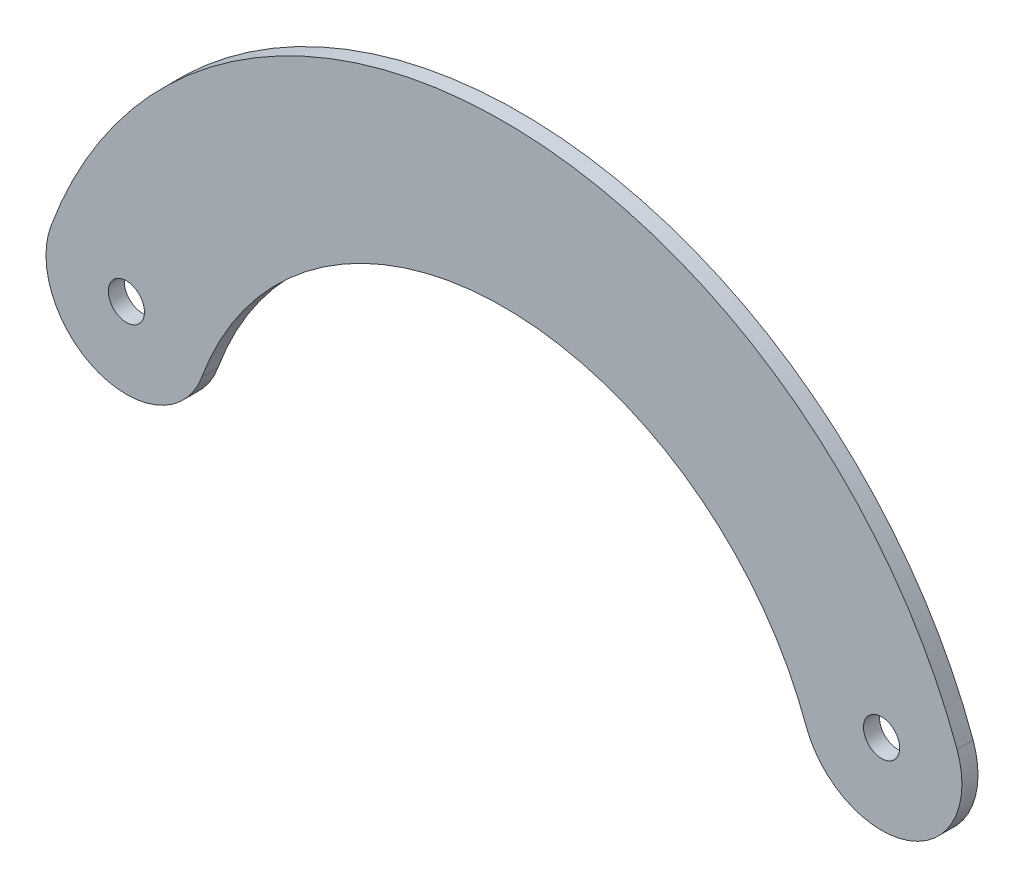
SolidWorks part; units mm, degrees
material "POLYURETHANE (11671)"
ref_plane "Face" through (0, 0, 0) normal (0, 0, 1) x (1, 0, 0)
ref_plane "Dessus" through (0, 0, 0) normal (0, 1, 0) x (1, 0, 0)
ref_plane "Droite" through (0, 0, 0) normal (1, 0, 0) x (0, 0, -1)
sketch "Esquisse1" plane through (0, 0, 0) normal (0, 0, 1) x (1, 0, 0)
  line L0 (0, 0) -> (0, 50) construction
  line L1 (0, 0) -> (46.9846, 17.101) construction
  line L2 (0, 0) -> (-46.9846, 17.101) construction
  arc A0 (46.9846, 17.101) -> (-46.9846, 17.101) centre (0, 0) ccw construction
  arc A1 (37.5877, 13.6808) -> (56.3816, 20.5212) centre (46.9846, 17.101) ccw
  arc A2 (-56.3816, 20.5212) -> (-37.5877, 13.6808) centre (-46.9846, 17.101) ccw
  arc A3 (37.5877, 13.6808) -> (-37.5877, 13.6808) centre (0, 0) ccw
  arc A4 (56.3816, 20.5212) -> (-56.3816, 20.5212) centre (0, 0) ccw
  circle A5 centre (-46.9846, 17.101) radius 2.25
  circle A6 centre (46.9846, 17.101) radius 2.25
  dimension "D1" = 70
  dimension "D2" = 70
  dimension "D5" = 4.5
  dimension "D6" = 50
  dimension "D3" = 10
  dimension "D4" = 4.5
extrude "Boss.-Extru.1" add sketch "Esquisse1" along normal blind 2
sketch "Graduations" plane through (0, 0, 2) normal (0, 0, 1) x (1, 0, 0)
  line L0 (0, 45) -> (0, 53)
  line L1 (7.8142, 44.3163) -> (9.2034, 52.1948)
  line L2 (15.3909, 42.2862) -> (18.1271, 49.8037)
  line L3 (22.5, 38.9711) -> (26.5, 45.8993)
  line L4 (28.9254, 34.472) -> (34.0677, 40.6004)
  line L5 (34.472, 28.9254) -> (40.6004, 34.0677)
  line L6 (38.9711, 22.5) -> (45.8993, 26.5)
  line L8 (11.6469, 43.4667) -> (12.6821, 47.3304)
  line L9 (-38.5725, 23.1767) -> (-40.7154, 24.4643)
  line L10 (19.0178, 40.7839) -> (20.7083, 44.4091)
  line L11 (-38.1622, 23.8464) -> (-40.2823, 25.1712)
  line L12 (3.922, 44.8288) -> (4.2706, 48.8135)
  line L13 (25.8109, 36.8618) -> (28.1052, 40.1385)
  line L14 (-37.7402, 24.5088) -> (-39.8369, 25.8704)
  line L15 (31.8198, 31.8198) -> (34.6482, 34.6482)
  line L16 (-37.3067, 25.1637) -> (-39.3793, 26.5617)
  line L17 (36.8618, 25.8109) -> (40.1385, 28.1052)
  line L19 (-36.4058, 26.4503) -> (-38.4283, 27.9198)
  line L20 (-35.9386, 27.0817) -> (-37.9352, 28.5862)
  line L21 (-35.4605, 27.7048) -> (-37.4305, 29.2439)
  line L22 (-34.9716, 28.3194) -> (-36.9144, 29.8927)
  line L24 (-33.9619, 29.5227) -> (-35.8487, 31.1628)
  line L25 (-33.4415, 30.1109) -> (-35.2994, 31.7837)
  line L26 (-32.9109, 30.6899) -> (-34.7393, 32.3949)
  line L27 (-32.3703, 31.2596) -> (-34.1686, 32.9963)
  line L29 (-31.2596, 32.3703) -> (-32.9963, 34.1686)
  line L30 (-38.9711, 22.5) -> (-45.8993, 26.5)
  line L31 (-34.472, 28.9254) -> (-40.6004, 34.0677)
  line L32 (-28.9254, 34.472) -> (-34.0677, 40.6004)
  line L33 (-22.5, 38.9711) -> (-26.5, 45.8993)
  line L34 (-15.3909, 42.2862) -> (-18.1271, 49.8037)
  line L35 (-7.8142, 44.3163) -> (-9.2034, 52.1948)
  line L36 (42.2862, 15.3909) -> (49.8037, 18.1271)
  line L37 (-42.2862, 15.3909) -> (-49.8037, 18.1271)
  line L38 (44.3163, 7.8142) -> (52.1948, 9.2034)
  line L39 (45, 0) -> (53, 0)
  line L40 (44.3163, -7.8142) -> (52.1948, -9.2034)
  line L41 (42.2862, -15.3909) -> (49.8037, -18.1271)
  line L42 (38.9711, -22.5) -> (45.8993, -26.5)
  line L43 (34.472, -28.9254) -> (40.6004, -34.0677)
  line L44 (28.9254, -34.472) -> (34.0677, -40.6004)
  line L45 (22.5, -38.9711) -> (26.5, -45.8993)
  line L46 (15.3909, -42.2862) -> (18.1271, -49.8037)
  line L47 (7.8142, -44.3163) -> (9.2034, -52.1948)
  line L48 (0, -45) -> (0, -53)
  line L49 (-7.8142, -44.3163) -> (-9.2034, -52.1948)
  line L50 (-15.3909, -42.2862) -> (-18.1271, -49.8037)
  line L51 (-22.5, -38.9711) -> (-26.5, -45.8993)
  line L52 (-28.9254, -34.472) -> (-34.0677, -40.6004)
  line L53 (-34.472, -28.9254) -> (-40.6004, -34.0677)
  line L54 (-38.9711, -22.5) -> (-45.8993, -26.5)
  line L55 (-42.2862, -15.3909) -> (-49.8037, -18.1271)
  line L56 (-44.3163, -7.8142) -> (-52.1948, -9.2034)
  line L57 (-45, 0) -> (-53, 0)
  line L58 (-44.3163, 7.8142) -> (-52.1948, 9.2034)
  line L59 (-30.6899, 32.9109) -> (-32.3949, 34.7393)
  line L60 (-30.1109, 33.4415) -> (-31.7837, 35.2994)
  line L61 (-29.5227, 33.9619) -> (-31.1628, 35.8487)
  line L63 (-28.3194, 34.9716) -> (-29.8927, 36.9144)
  line L64 (-27.7048, 35.4605) -> (-29.2439, 37.4305)
  line L65 (-27.0817, 35.9386) -> (-28.5862, 37.9352)
  line L66 (-26.4503, 36.4058) -> (-27.9198, 38.4283)
  line L68 (-25.1637, 37.3067) -> (-26.5617, 39.3793)
  line L69 (-24.5088, 37.7402) -> (-25.8704, 39.8369)
  line L70 (-23.8464, 38.1622) -> (-25.1712, 40.2823)
  line L71 (-23.1767, 38.5725) -> (-24.4643, 40.7154)
  line L73 (-21.8164, 39.3579) -> (-23.0285, 41.5444)
  line L74 (-21.1262, 39.7326) -> (-22.2999, 41.94)
  line L75 (-20.4296, 40.0953) -> (-21.5645, 42.3228)
  line L76 (-19.7267, 40.4457) -> (-20.8226, 42.6927)
  line L78 (-18.3031, 41.1095) -> (-19.32, 43.3934)
  line L79 (-17.5829, 41.4227) -> (-18.5597, 43.724)
  line L80 (-16.8573, 41.7233) -> (-17.7938, 44.0412)
  line L81 (-16.1266, 42.0111) -> (-17.0225, 44.3451)
  line L83 (-14.6506, 42.5483) -> (-15.4645, 44.9121)
  line L84 (-13.9058, 42.7975) -> (-14.6783, 45.1752)
  line L85 (-13.1567, 43.0337) -> (-13.8877, 45.4245)
  line L86 (-12.4037, 43.2568) -> (-13.0928, 45.6599)
  line L88 (-10.8865, 43.6633) -> (-11.4913, 46.089)
  line L89 (-10.1228, 43.8467) -> (-10.6852, 46.2826)
  line L90 (-9.356, 44.0166) -> (-9.8758, 46.462)
  line L91 (-8.5864, 44.1732) -> (-9.0634, 46.6273)
  line L93 (-7.0396, 44.446) -> (-7.4306, 46.9152)
  line L94 (-6.2628, 44.5621) -> (-6.6107, 47.0377)
  line L95 (-5.4841, 44.6646) -> (-5.7888, 47.1459)
  line L96 (-4.7038, 44.7535) -> (-4.9651, 47.2398)
  line L98 (-3.139, 44.8904) -> (-3.3134, 47.3843)
  line L99 (-2.3551, 44.9383) -> (-2.486, 47.4349)
  line L100 (-1.5705, 44.9726) -> (-1.6577, 47.4711)
  line L101 (-0.7854, 44.9931) -> (-0.829, 47.4928)
  line L103 (0.7854, 44.9931) -> (0.829, 47.4928)
  line L104 (-36.8618, 25.8109) -> (-40.1385, 28.1052)
  line L105 (1.5705, 44.9726) -> (1.6577, 47.4711)
  line L106 (-31.8198, 31.8198) -> (-34.6482, 34.6482)
  line L107 (2.3551, 44.9383) -> (2.486, 47.4349)
  line L108 (-25.8109, 36.8618) -> (-28.1052, 40.1385)
  line L109 (3.139, 44.8904) -> (3.3134, 47.3843)
  line L110 (-19.0178, 40.7839) -> (-20.7083, 44.4091)
  line L112 (-11.6469, 43.4667) -> (-12.6821, 47.3304)
  line L113 (4.7038, 44.7535) -> (4.9651, 47.2398)
  line L114 (-3.922, 44.8288) -> (-4.2706, 48.8135)
  line L115 (5.4841, 44.6646) -> (5.7888, 47.1459)
  line L116 (42.2862, 15.3909) -> (46.0449, 16.759)
  line L117 (43.4667, 11.6469) -> (47.3304, 12.6821)
  line L118 (44.3163, 7.8142) -> (48.2556, 8.5088)
  line L119 (44.8288, 3.922) -> (48.8135, 4.2706)
  line L120 (45, 0) -> (49, 0)
  line L121 (44.8288, -3.922) -> (48.8135, -4.2706)
  line L122 (44.3163, -7.8142) -> (48.2556, -8.5088)
  line L123 (43.4667, -11.6469) -> (47.3304, -12.6821)
  line L124 (42.2862, -15.3909) -> (46.0449, -16.759)
  line L125 (40.7839, -19.0178) -> (44.4091, -20.7083)
  line L126 (38.9711, -22.5) -> (42.4352, -24.5)
  line L127 (-38.9711, -22.5) -> (-42.4352, -24.5)
  line L128 (-40.7839, -19.0178) -> (-44.4091, -20.7083)
  line L129 (-42.2862, -15.3909) -> (-46.0449, -16.759)
  line L130 (-43.4667, -11.6469) -> (-47.3304, -12.6821)
  line L131 (-44.3163, -7.8142) -> (-48.2556, -8.5088)
  line L132 (-44.8288, -3.922) -> (-48.8135, -4.2706)
  line L133 (-45, 0) -> (-49, 0)
  line L134 (-44.8288, 3.922) -> (-48.8135, 4.2706)
  line L135 (-44.3163, 7.8142) -> (-48.2556, 8.5088)
  line L136 (-43.4667, 11.6469) -> (-47.3304, 12.6821)
  line L137 (-42.2862, 15.3909) -> (-46.0449, 16.759)
  line L138 (36.8618, -25.8109) -> (40.1385, -28.1052)
  line L139 (34.472, -28.9254) -> (37.5362, -31.4966)
  line L140 (31.8198, -31.8198) -> (34.6482, -34.6482)
  line L141 (28.9254, -34.472) -> (31.4966, -37.5362)
  line L142 (25.8109, -36.8618) -> (28.1052, -40.1385)
  line L143 (22.5, -38.9711) -> (24.5, -42.4352)
  line L144 (19.0178, -40.7839) -> (20.7083, -44.4091)
  line L145 (15.3909, -42.2862) -> (16.759, -46.0449)
  line L146 (11.6469, -43.4667) -> (12.6821, -47.3304)
  line L147 (7.8142, -44.3163) -> (8.5088, -48.2556)
  line L148 (3.922, -44.8288) -> (4.2706, -48.8135)
  line L149 (0, -45) -> (0, -49)
  line L150 (-3.922, -44.8288) -> (-4.2706, -48.8135)
  line L151 (-7.8142, -44.3163) -> (-8.5088, -48.2556)
  line L152 (-11.6469, -43.4667) -> (-12.6821, -47.3304)
  line L153 (-15.3909, -42.2862) -> (-16.759, -46.0449)
  line L154 (-19.0178, -40.7839) -> (-20.7083, -44.4091)
  line L155 (-22.5, -38.9711) -> (-24.5, -42.4352)
  line L156 (-25.8109, -36.8618) -> (-28.1052, -40.1385)
  line L157 (-28.9254, -34.472) -> (-31.4966, -37.5362)
  line L158 (-31.8198, -31.8198) -> (-34.6482, -34.6482)
  line L159 (-34.472, -28.9254) -> (-37.5362, -31.4966)
  line L160 (-36.8618, -25.8109) -> (-40.1385, -28.1052)
  line L161 (-40.7839, 19.0178) -> (-44.4091, 20.7083)
  line L162 (40.7839, 19.0178) -> (44.4091, 20.7083)
  line L163 (38.9711, 22.5) -> (42.4352, 24.5)
  line L164 (34.472, 28.9254) -> (37.5362, 31.4966)
  line L165 (28.9254, 34.472) -> (31.4966, 37.5362)
  line L166 (22.5, 38.9711) -> (24.5, 42.4352)
  line L167 (15.3909, 42.2862) -> (16.759, 46.0449)
  line L168 (7.8142, 44.3163) -> (8.5088, 48.2556)
  line L169 (0, 45) -> (0, 49)
  line L170 (-7.8142, 44.3163) -> (-8.5088, 48.2556)
  line L171 (-15.3909, 42.2862) -> (-16.759, 46.0449)
  line L172 (-22.5, 38.9711) -> (-24.5, 42.4352)
  line L173 (-28.9254, 34.472) -> (-31.4966, 37.5362)
  line L174 (-34.472, 28.9254) -> (-37.5362, 31.4966)
  line L175 (-38.9711, 22.5) -> (-42.4352, 24.5)
  line L176 (6.2628, 44.5621) -> (6.6107, 47.0377)
  line L177 (7.0396, 44.446) -> (7.4306, 46.9152)
  line L179 (8.5864, 44.1732) -> (9.0634, 46.6273)
  line L180 (9.356, 44.0166) -> (9.8758, 46.462)
  line L181 (10.1228, 43.8467) -> (10.6852, 46.2826)
  line L182 (10.8865, 43.6633) -> (11.4913, 46.089)
  line L184 (12.4037, 43.2568) -> (13.0928, 45.6599)
  line L185 (13.1567, 43.0337) -> (13.8877, 45.4245)
  line L186 (13.9058, 42.7975) -> (14.6783, 45.1752)
  line L187 (14.6506, 42.5483) -> (15.4645, 44.9121)
  line L189 (16.1266, 42.0111) -> (17.0225, 44.3451)
  line L190 (16.8573, 41.7233) -> (17.7938, 44.0412)
  line L191 (17.5829, 41.4227) -> (18.5597, 43.724)
  line L192 (18.3031, 41.1095) -> (19.32, 43.3934)
  line L194 (19.7267, 40.4457) -> (20.8226, 42.6927)
  line L195 (20.4296, 40.0953) -> (21.5645, 42.3228)
  line L196 (21.1262, 39.7326) -> (22.2999, 41.94)
  line L197 (21.8164, 39.3579) -> (23.0285, 41.5444)
  line L199 (23.1767, 38.5725) -> (24.4643, 40.7154)
  line L200 (23.8464, 38.1622) -> (25.1712, 40.2823)
  line L201 (24.5088, 37.7402) -> (25.8704, 39.8369)
  line L202 (25.1637, 37.3067) -> (26.5617, 39.3793)
  line L204 (26.4503, 36.4058) -> (27.9198, 38.4283)
  line L205 (27.0817, 35.9386) -> (28.5862, 37.9352)
  line L206 (27.7048, 35.4605) -> (29.2439, 37.4305)
  line L207 (28.3194, 34.9716) -> (29.8927, 36.9144)
  line L209 (29.5227, 33.9619) -> (31.1628, 35.8487)
  line L210 (30.1109, 33.4415) -> (31.7837, 35.2994)
  line L211 (30.6899, 32.9109) -> (32.3949, 34.7393)
  line L212 (31.2596, 32.3703) -> (32.9963, 34.1686)
  line L214 (32.3703, 31.2596) -> (34.1686, 32.9963)
  line L215 (32.9109, 30.6899) -> (34.7393, 32.3949)
  line L216 (33.4415, 30.1109) -> (35.2994, 31.7837)
  line L217 (33.9619, 29.5227) -> (35.8487, 31.1628)
  line L219 (34.9716, 28.3194) -> (36.9144, 29.8927)
  line L220 (35.4605, 27.7048) -> (37.4305, 29.2439)
  line L221 (35.9386, 27.0817) -> (37.9352, 28.5862)
  line L222 (36.4058, 26.4503) -> (38.4283, 27.9198)
  line L224 (37.3067, 25.1637) -> (39.3793, 26.5617)
  line L225 (37.7402, 24.5088) -> (39.8369, 25.8704)
  line L226 (38.1622, 23.8464) -> (40.2823, 25.1712)
  line L227 (38.5725, 23.1767) -> (40.7154, 24.4643)
  arc A0 (38.9711, 22.5) -> (-38.9711, 22.5) centre (0, 0) ccw
  point P461 (0, 0)
  dimension "D1" = 36
  dimension "D2" = 72
